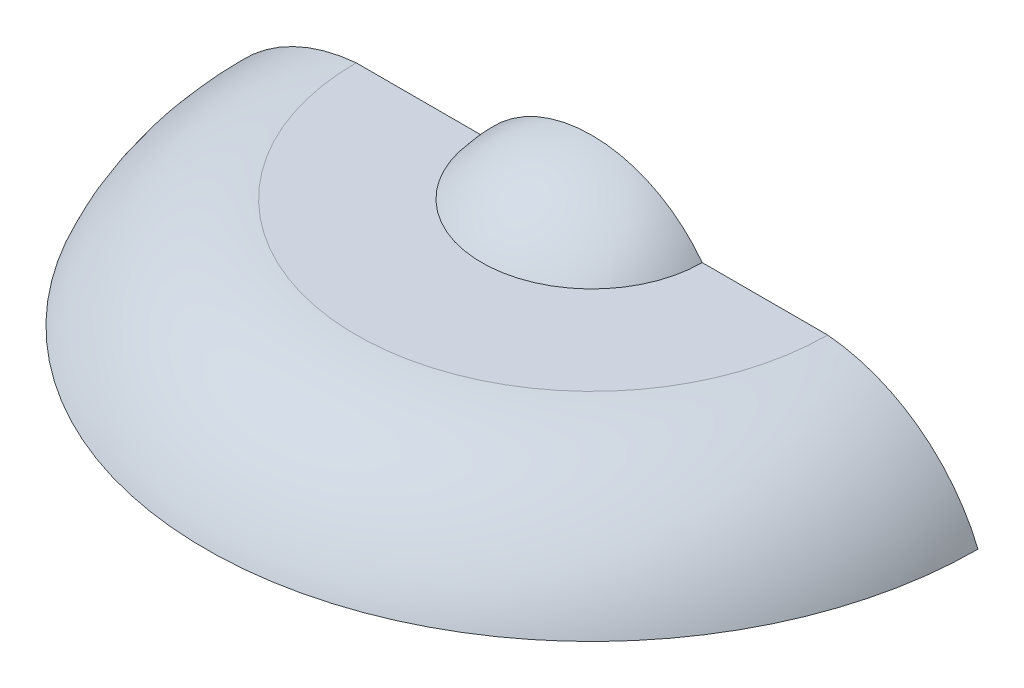
SolidWorks part; units mm, degrees
material "1060 Alloy"
ref_plane "Front Plane" through (0, 0, 0) normal (0, 0, 1) x (1, 0, 0)
ref_plane "Top Plane" through (0, 0, 0) normal (0, 1, 0) x (1, 0, 0)
ref_plane "Right Plane" through (0, 0, 0) normal (1, 0, 0) x (0, 0, -1)
sketch "Sketch1" plane through (0, 0, 0) normal (0, 0, 1) x (1, 0, 0)
  line L0 (0, 0) -> (88.9, 0)
  line L5 (0, 38.1) -> (0, 0)
  line L6 (54.279, 25.4) -> (25.4, 25.4)
  arc A0 (54.279, 25.4) -> (88.9, 0) centre (50.7369, -15.7227) cw
  arc A1 (0, 38.1) -> (25.4, 25.4) centre (0, 6.35) cw
  dimension "D4" = 31.75
  dimension "D5" = 41.275
  dimension "D6" = 15.7227
  dimension "D1" = 88.9
  dimension "D2" = 38.1
  dimension "D3" = 12.7
revolve "Revolve1" add sketch "Sketch1" angle 180 about L5
